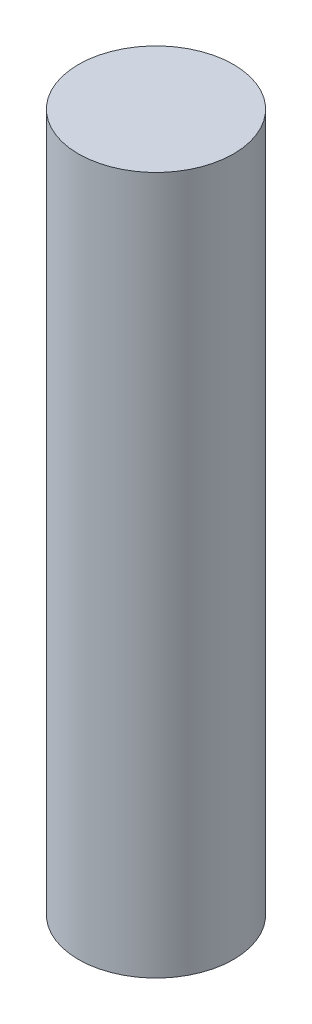
SolidWorks part; units mm, degrees
ref_plane "Front Plane" through (0, 0, 0) normal (0, 0, 1) x (1, 0, 0)
ref_plane "Top Plane" through (0, 0, 0) normal (0, 1, 0) x (1, 0, 0)
ref_plane "Right Plane" through (0, 0, 0) normal (1, 0, 0) x (0, 0, -1)
sketch "Sketch1" plane through (0, 0, 0) normal (0, 1, 0) x (1, 0, 0)
  circle A0 centre (0, 0) radius 3
  dimension "D1" = 6
extrude "Boss-Extrude1" add sketch "Sketch1" along normal blind 27
